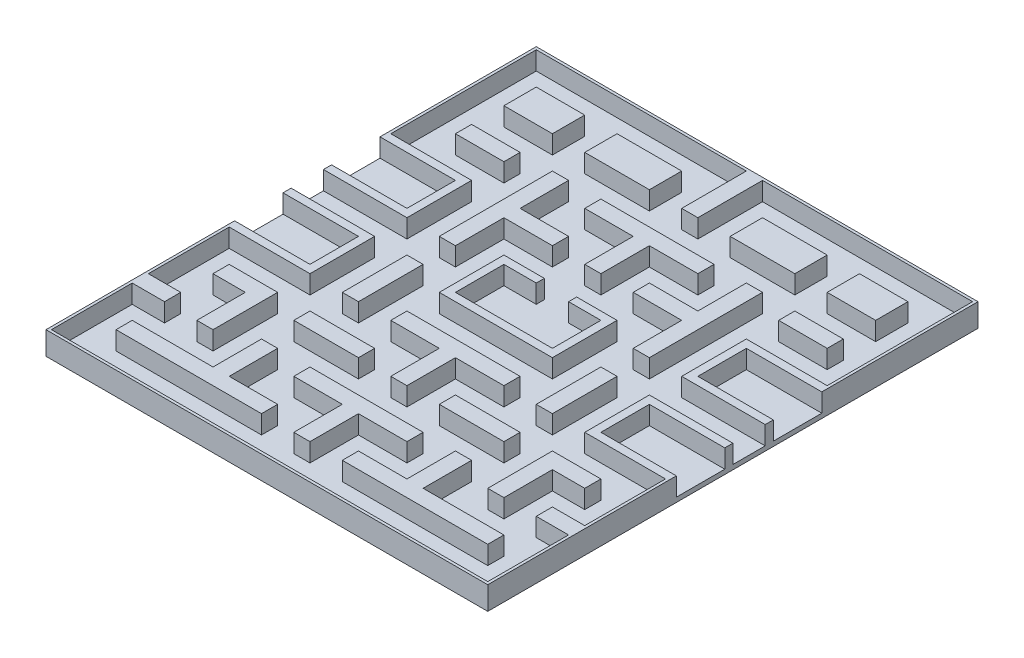
SolidWorks part; units mm, degrees
ref_plane "Front Plane" through (0, 0, 0) normal (0, 0, 1) x (1, 0, 0)
ref_plane "Top Plane" through (0, 0, 0) normal (0, 1, 0) x (1, 0, 0)
ref_plane "Right Plane" through (0, 0, 0) normal (1, 0, 0) x (0, 0, -1)
sketch "Sketch1" plane through (0, 0, 0) normal (0, 1, 0) x (1, 0, 0)
  line L1 (-1244.6, 1600.2) -> (1244.6, 1600.2)
  line L2 (-1244.6, 1600.2) -> (-1244.6, -1600.2)
  line L3 (-1244.6, -1600.2) -> (1244.6, -1600.2)
  line L4 (1244.6, 1600.2) -> (1244.6, -1600.2)
  line L5 (-1244.6, 1600.2) -> (1244.6, -1600.2) construction
  line L6 (-1244.6, -1600.2) -> (1244.6, 1600.2) construction
  point P0 (0, 0)
  dimension "D1" = 3200.4
  dimension "D2" = 2489.2
extrude "Boss-Extrude2" add sketch "Sketch1" along normal blind 25.4
sketch "Sketch5" plane through (0, 25.4, 0) normal (0, 1, 0) x (1, 0, 0)
  line L0 (-1155.7, 1600.2) -> (-1155.7, -1600.2)
  line L1 (1244.6, 1600.2) -> (-1244.6, 1600.2) construction
  line L2 (-1244.6, -1600.2) -> (1244.6, -1600.2) construction
  line L3 (-1244.6, 1600.2) -> (-1244.6, -1600.2) construction
  line L4 (-1066.8, 1600.2) -> (-1066.8, -1600.2)
  line L5 (-977.9, 1600.2) -> (-977.9, -1600.2)
  line L6 (-889, 1600.2) -> (-889, -1600.2)
  line L7 (-800.1, 1600.2) -> (-800.1, -1600.2)
  line L8 (-711.2, 1600.2) -> (-711.2, -1600.2)
  line L9 (-622.3, 1600.2) -> (-622.3, -1600.2)
  line L10 (-533.4, 1600.2) -> (-533.4, -1600.2)
  line L11 (-444.5, 1600.2) -> (-444.5, -1600.2)
  line L12 (-355.6, 1600.2) -> (-355.6, -1600.2)
  line L13 (-266.7, 1600.2) -> (-266.7, -1600.2)
  line L14 (-177.8, 1600.2) -> (-177.8, -1600.2)
  line L15 (-88.9, 1600.2) -> (-88.9, -1600.2)
  line L16 (0, 1600.2) -> (0, -1600.2)
  line L17 (88.9, 1600.2) -> (88.9, -1600.2)
  line L18 (177.8, 1600.2) -> (177.8, -1600.2)
  line L19 (266.7, 1600.2) -> (266.7, -1600.2)
  line L20 (355.6, 1600.2) -> (355.6, -1600.2)
  line L21 (444.5, 1600.2) -> (444.5, -1600.2)
  line L22 (533.4, 1600.2) -> (533.4, -1600.2)
  line L23 (622.3, 1600.2) -> (622.3, -1600.2)
  line L24 (711.2, 1600.2) -> (711.2, -1600.2)
  line L25 (800.1, 1600.2) -> (800.1, -1600.2)
  line L26 (889, 1600.2) -> (889, -1600.2)
  line L27 (977.9, 1600.2) -> (977.9, -1600.2)
  line L28 (1066.8, 1600.2) -> (1066.8, -1600.2)
  line L29 (1155.7, 1600.2) -> (1155.7, -1600.2)
  line L30 (-1244.6, -1511.3) -> (1244.6, -1511.3)
  line L31 (1244.6, -1600.2) -> (1244.6, 1600.2) construction
  line L32 (-1244.6, -1422.4) -> (1244.6, -1422.4)
  line L33 (-1244.6, -1333.5) -> (1244.6, -1333.5)
  line L34 (-1244.6, -1244.6) -> (1244.6, -1244.6)
  line L35 (-1244.6, -1155.7) -> (1244.6, -1155.7)
  line L36 (-1244.6, -1066.8) -> (1244.6, -1066.8)
  line L37 (-1244.6, -977.9) -> (1244.6, -977.9)
  line L38 (-1244.6, -889) -> (1244.6, -889)
  line L39 (-1244.6, -800.1) -> (1244.6, -800.1)
  line L40 (-1244.6, -711.2) -> (1244.6, -711.2)
  line L41 (-1244.6, -622.3) -> (1244.6, -622.3)
  line L42 (-1244.6, -533.4) -> (1244.6, -533.4)
  line L43 (-1244.6, -444.5) -> (1244.6, -444.5)
  line L44 (-1244.6, -355.6) -> (1244.6, -355.6)
  line L45 (-1244.6, -266.7) -> (1244.6, -266.7)
  line L46 (-1244.6, -177.8) -> (1244.6, -177.8)
  line L47 (-1244.6, -88.9) -> (1244.6, -88.9)
  line L48 (-1244.6, 0) -> (1244.6, 0)
  line L49 (-1244.6, 88.9) -> (1244.6, 88.9)
  line L50 (-1244.6, 177.8) -> (1244.6, 177.8)
  line L51 (-1244.6, 266.7) -> (1244.6, 266.7)
  line L52 (-1244.6, 355.6) -> (1244.6, 355.6)
  line L53 (-1244.6, 444.5) -> (1244.6, 444.5)
  line L54 (-1244.6, 533.4) -> (1244.6, 533.4)
  line L55 (-1244.6, 622.3) -> (1244.6, 622.3)
  line L56 (-1244.6, 711.2) -> (1244.6, 711.2)
  line L57 (-1244.6, 800.1) -> (1244.6, 800.1)
  line L58 (-1244.6, 889) -> (1244.6, 889)
  line L59 (-1244.6, 977.9) -> (1244.6, 977.9)
  line L60 (-1244.6, 1066.8) -> (1244.6, 1066.8)
  line L61 (-1244.6, 1155.7) -> (1244.6, 1155.7)
  line L62 (-1244.6, 1244.6) -> (1244.6, 1244.6)
  line L63 (-1244.6, 1333.5) -> (1244.6, 1333.5)
  line L64 (-1244.6, 1422.4) -> (1244.6, 1422.4)
  line L65 (-1244.6, 1511.3) -> (1244.6, 1511.3)
  dimension "D1" = 88.9
  dimension "D3" = 88.9
  dimension "D2" = 27
  dimension "D4" = 35
sketch "Sketch6" plane through (0, 25.4, 0) normal (0, 1, 0) x (1, 0, 0)
  line L0 (-1244.6, 1333.5) -> (1244.6, 1333.5)
  line L1 (-88.9, 222.25) -> (-88.9, 177.8)
  line L2 (755.65, -44.45) -> (755.65, -400.05)
  line L3 (1200.15, -400.05) -> (1200.15, -844.55)
  line L4 (-1244.6, 444.5) -> (1244.6, 444.5) construction
  line L5 (755.65, -400.05) -> (1200.15, -400.05)
  line L6 (-1244.6, 177.8) -> (1244.6, 177.8) construction
  line L7 (755.65, -44.45) -> (1244.6, -44.45)
  line L8 (1244.6, 133.35) -> (755.65, 133.35)
  line L9 (755.65, 488.95) -> (755.65, 133.35)
  line L10 (-1244.6, -88.9) -> (1244.6, -88.9) construction
  line L11 (1200.15, 488.95) -> (755.65, 488.95)
  line L12 (-1244.6, -355.6) -> (1244.6, -355.6) construction
  line L13 (1200.15, 1289.05) -> (1200.15, 488.95)
  line L14 (1244.6, 444.5) -> (1244.6, 1333.5)
  line L15 (1244.6, -1422.4) -> (-1244.6, -1422.4)
  line L16 (-1244.6, -1422.4) -> (-1244.6, -355.6)
  line L17 (-1244.6, -355.6) -> (-800.1, -355.6)
  line L18 (-800.1, 1600.2) -> (-800.1, -1600.2) construction
  line L19 (-800.1, -355.6) -> (-800.1, -88.9)
  line L20 (-800.1, -88.9) -> (-1244.6, -88.9)
  line L21 (-1244.6, -88.9) -> (-1244.6, 177.8)
  line L22 (-1244.6, 177.8) -> (-800.1, 177.8)
  line L23 (-800.1, 177.8) -> (-800.1, 444.5)
  line L24 (-800.1, 444.5) -> (-1244.6, 444.5)
  line L25 (-1244.6, 444.5) -> (-1244.6, 1333.5)
  line L26 (-1200.15, 1289.05) -> (-44.45, 1289.05)
  line L27 (800.1, 444.5) -> (1244.6, 444.5)
  line L28 (-1200.15, 1289.05) -> (-1200.15, 488.95)
  line L29 (-1200.15, 488.95) -> (-755.65, 488.95)
  line L30 (-755.65, 488.95) -> (-755.65, 133.35)
  line L31 (-1244.6, 133.35) -> (-755.65, 133.35)
  line L32 (-755.65, -44.45) -> (-1244.6, -44.45)
  line L33 (-755.65, -400.05) -> (-1200.15, -400.05)
  line L34 (-1200.15, -400.05) -> (-1200.15, -844.55)
  line L35 (-1200.15, -1377.95) -> (1200.15, -1377.95)
  line L36 (-1244.6, 622.3) -> (1244.6, 622.3) construction
  line L37 (800.1, 177.8) -> (800.1, 444.5)
  line L38 (-755.65, -44.45) -> (-755.65, -400.05)
  line L39 (88.9, 177.8) -> (88.9, 222.25)
  line L40 (-1200.15, -844.55) -> (-1022.35, -844.55)
  line L41 (1244.6, 177.8) -> (800.1, 177.8)
  line L42 (1244.6, -88.9) -> (1244.6, 177.8)
  line L43 (800.1, -88.9) -> (1244.6, -88.9)
  line L44 (800.1, -355.6) -> (800.1, -88.9)
  line L45 (1244.6, -355.6) -> (800.1, -355.6)
  line L46 (1244.6, -1422.4) -> (1244.6, -355.6)
  line L47 (177.8, 1600.2) -> (177.8, -1600.2) construction
  line L48 (-1022.35, -844.55) -> (-1022.35, -933.45)
  line L49 (-1022.35, -933.45) -> (-1200.15, -933.45)
  line L50 (-1244.6, -800.1) -> (1244.6, -800.1) construction
  line L51 (-1200.15, -933.45) -> (-1200.15, -1377.95)
  line L52 (1200.15, -844.55) -> (1022.35, -844.55)
  line L53 (1022.35, -933.45) -> (1200.15, -933.45)
  line L54 (1022.35, -844.55) -> (1022.35, -933.45)
  line L55 (1200.15, -933.45) -> (1200.15, -1377.95)
  line L56 (-1022.35, 1111.25) -> (-755.65, 1111.25)
  line L57 (-755.65, 1111.25) -> (-755.65, 933.45)
  line L58 (-755.65, 933.45) -> (-1022.35, 933.45)
  line L59 (-1022.35, 933.45) -> (-1022.35, 1111.25)
  line L60 (-577.85, 1111.25) -> (-222.25, 1111.25)
  line L61 (-222.25, 1111.25) -> (-222.25, 933.45)
  line L62 (-222.25, 933.45) -> (-577.85, 933.45)
  line L63 (-577.85, 933.45) -> (-577.85, 1111.25)
  line L64 (-1022.35, 755.65) -> (-755.65, 755.65)
  line L65 (-755.65, 755.65) -> (-755.65, 666.75)
  line L66 (-755.65, 666.75) -> (-1022.35, 666.75)
  line L67 (-1022.35, 666.75) -> (-1022.35, 755.65)
  line L68 (-577.85, 755.65) -> (-577.85, 133.35)
  line L69 (-577.85, 133.35) -> (-488.95, 133.35)
  line L70 (-488.95, 133.35) -> (-488.95, 400.05)
  line L71 (-488.95, 400.05) -> (-222.25, 400.05)
  line L72 (-222.25, 400.05) -> (-222.25, 488.95)
  line L73 (-222.25, 488.95) -> (-488.95, 488.95)
  line L74 (-488.95, 488.95) -> (-488.95, 755.65)
  line L75 (-488.95, 755.65) -> (-577.85, 755.65)
  line L76 (-1244.6, 800.1) -> (1244.6, 800.1) construction
  line L77 (-577.85, -44.45) -> (-488.95, -44.45)
  line L78 (-488.95, -44.45) -> (-488.95, -400.05)
  line L79 (-488.95, -400.05) -> (-577.85, -400.05)
  line L80 (-577.85, -400.05) -> (-577.85, -44.45)
  line L81 (-622.3, 1600.2) -> (-622.3, -1600.2) construction
  line L82 (-844.55, -933.45) -> (-755.65, -933.45)
  line L83 (-577.85, -577.85) -> (-222.25, -577.85)
  line L84 (-222.25, -577.85) -> (-222.25, -666.75)
  line L85 (-222.25, -666.75) -> (-577.85, -666.75)
  line L86 (-577.85, -666.75) -> (-577.85, -577.85)
  line L87 (-1244.6, -533.4) -> (1244.6, -533.4) construction
  line L88 (-755.65, -577.85) -> (-1022.35, -577.85)
  line L89 (-1022.35, -577.85) -> (-1022.35, -666.75)
  line L90 (-1022.35, -666.75) -> (-844.55, -666.75)
  line L91 (-844.55, -666.75) -> (-844.55, -933.45)
  line L92 (-755.65, -933.45) -> (-755.65, -577.85)
  line L93 (-1066.8, 1600.2) -> (-1066.8, -1600.2) construction
  line L94 (-577.85, -844.55) -> (-577.85, -1111.25)
  line L95 (-577.85, -1111.25) -> (-1022.35, -1111.25)
  line L96 (-1022.35, -1111.25) -> (-1022.35, -1200.15)
  line L97 (-1022.35, -1200.15) -> (-222.25, -1200.15)
  line L98 (-222.25, -1200.15) -> (-222.25, -1111.25)
  line L99 (-222.25, -1111.25) -> (-488.95, -1111.25)
  line L100 (-488.95, -1111.25) -> (-488.95, -844.55)
  line L101 (-488.95, -844.55) -> (-577.85, -844.55)
  line L102 (-1244.6, -1066.8) -> (1244.6, -1066.8) construction
  line L103 (-311.15, -400.05) -> (-311.15, -311.15)
  line L104 (-311.15, -311.15) -> (311.15, -311.15)
  line L105 (-311.15, -400.05) -> (-44.45, -400.05)
  line L106 (-44.45, -400.05) -> (-44.45, -666.75)
  line L107 (-44.45, -666.75) -> (44.45, -666.75)
  line L108 (-1244.6, -444.5) -> (1244.6, -444.5) construction
  line L109 (-355.6, 1600.2) -> (-355.6, -1600.2) construction
  line L110 (-311.15, -844.55) -> (311.15, -844.55)
  line L111 (-311.15, -844.55) -> (-311.15, -933.45)
  line L112 (-311.15, -933.45) -> (-44.45, -933.45)
  line L113 (-44.45, -933.45) -> (-44.45, -1200.15)
  line L114 (-44.45, -1200.15) -> (44.45, -1200.15)
  line L115 (-311.15, 755.65) -> (311.15, 755.65)
  line L116 (-311.15, 755.65) -> (-311.15, 666.75)
  line L117 (-311.15, 666.75) -> (-44.45, 666.75)
  line L118 (-44.45, 400.05) -> (44.45, 400.05)
  line L119 (-44.45, 400.05) -> (-44.45, 666.75)
  line L120 (355.6, 1600.2) -> (355.6, -1600.2) construction
  line L121 (-311.15, -133.35) -> (-311.15, 222.25)
  line L122 (-311.15, 222.25) -> (-88.9, 222.25)
  line L123 (-88.9, 1600.2) -> (-88.9, -1600.2) construction
  line L124 (-311.15, -133.35) -> (311.15, -133.35)
  line L125 (-1244.6, 266.7) -> (1244.6, 266.7) construction
  line L126 (-88.9, 177.8) -> (-266.7, 177.8)
  line L127 (-266.7, 1600.2) -> (-266.7, -1600.2) construction
  line L128 (-266.7, 177.8) -> (-266.7, -88.9)
  line L129 (-266.7, -88.9) -> (266.7, -88.9)
  line L130 (-44.45, 933.45) -> (-44.45, 1289.05)
  line L131 (-44.45, 933.45) -> (44.45, 933.45)
  line L132 (-1244.6, 889) -> (1244.6, 889) construction
  line L133 (44.45, -933.45) -> (44.45, -1200.15)
  line L134 (311.15, -933.45) -> (44.45, -933.45)
  line L135 (311.15, -844.55) -> (311.15, -933.45)
  line L136 (488.95, -844.55) -> (577.85, -844.55)
  line L137 (488.95, -1111.25) -> (488.95, -844.55)
  line L138 (577.85, -844.55) -> (577.85, -1111.25)
  line L139 (222.25, -1111.25) -> (488.95, -1111.25)
  line L140 (222.25, -1200.15) -> (222.25, -1111.25)
  line L141 (1022.35, -1200.15) -> (222.25, -1200.15)
  line L142 (1022.35, -1111.25) -> (1022.35, -1200.15)
  line L143 (577.85, -1111.25) -> (1022.35, -1111.25)
  line L144 (844.55, -933.45) -> (755.65, -933.45)
  line L145 (844.55, -666.75) -> (844.55, -933.45)
  line L146 (755.65, -933.45) -> (755.65, -577.85)
  line L147 (1022.35, -666.75) -> (844.55, -666.75)
  line L148 (1022.35, -577.85) -> (1022.35, -666.75)
  line L149 (755.65, -577.85) -> (1022.35, -577.85)
  line L150 (577.85, -666.75) -> (577.85, -577.85)
  line L151 (222.25, -666.75) -> (577.85, -666.75)
  line L152 (577.85, -577.85) -> (222.25, -577.85)
  line L153 (44.45, -400.05) -> (44.45, -666.75)
  line L154 (311.15, -400.05) -> (44.45, -400.05)
  line L155 (311.15, -400.05) -> (311.15, -311.15)
  line L156 (222.25, -577.85) -> (222.25, -666.75)
  line L157 (577.85, -400.05) -> (577.85, -44.45)
  line L158 (488.95, -400.05) -> (577.85, -400.05)
  line L159 (488.95, -44.45) -> (488.95, -400.05)
  line L160 (577.85, -44.45) -> (488.95, -44.45)
  line L161 (266.7, 177.8) -> (266.7, -88.9)
  line L162 (88.9, 177.8) -> (266.7, 177.8)
  line L163 (311.15, 222.25) -> (88.9, 222.25)
  line L164 (311.15, -133.35) -> (311.15, 222.25)
  line L165 (44.45, 400.05) -> (44.45, 666.75)
  line L166 (311.15, 666.75) -> (44.45, 666.75)
  line L167 (311.15, 755.65) -> (311.15, 666.75)
  line L168 (488.95, 755.65) -> (577.85, 755.65)
  line L169 (488.95, 488.95) -> (488.95, 755.65)
  line L170 (222.25, 488.95) -> (488.95, 488.95)
  line L171 (222.25, 400.05) -> (222.25, 488.95)
  line L172 (488.95, 400.05) -> (222.25, 400.05)
  line L173 (488.95, 133.35) -> (488.95, 400.05)
  line L174 (577.85, 133.35) -> (488.95, 133.35)
  line L175 (577.85, 755.65) -> (577.85, 133.35)
  line L176 (1022.35, 666.75) -> (1022.35, 755.65)
  line L177 (755.65, 666.75) -> (1022.35, 666.75)
  line L178 (755.65, 755.65) -> (755.65, 666.75)
  line L179 (1022.35, 755.65) -> (755.65, 755.65)
  line L180 (44.45, 933.45) -> (44.45, 1289.05)
  line L181 (577.85, 933.45) -> (577.85, 1111.25)
  line L182 (222.25, 933.45) -> (577.85, 933.45)
  line L183 (222.25, 1111.25) -> (222.25, 933.45)
  line L184 (577.85, 1111.25) -> (222.25, 1111.25)
  line L185 (1022.35, 933.45) -> (1022.35, 1111.25)
  line L186 (755.65, 933.45) -> (1022.35, 933.45)
  line L187 (755.65, 1111.25) -> (755.65, 933.45)
  line L188 (1022.35, 1111.25) -> (755.65, 1111.25)
  line L189 (44.45, 1289.05) -> (1200.15, 1289.05)
  line L190 (-1244.6, 1155.7) -> (1244.6, 1155.7) construction
  line L191 (711.2, 1600.2) -> (711.2, -1600.2) construction
  line L192 (1155.7, 1600.2) -> (1155.7, -1600.2) construction
  line L193 (88.9, 1600.2) -> (88.9, -1600.2) construction
  line L194 (1244.6, -1600.2) -> (1244.6, 1600.2) construction
  line L195 (-1244.6, -977.9) -> (1244.6, -977.9) construction
  line L196 (444.5, 1600.2) -> (444.5, -1600.2) construction
  line L197 (622.3, 1600.2) -> (622.3, -1600.2) construction
  line L198 (266.7, 1600.2) -> (266.7, -1600.2) construction
  line L199 (0, 1600.2) -> (0, -1600.2) construction
  line L200 (-1244.6, -1244.6) -> (1244.6, -1244.6) construction
  line L201 (-1244.6, 0) -> (1244.6, 0) construction
  line L202 (1066.8, 1600.2) -> (1066.8, -1600.2) construction
  line L203 (-1244.6, 88.9) -> (1244.6, 88.9) construction
  line L204 (977.9, 1600.2) -> (977.9, -1600.2) construction
  line L205 (-1244.6, -711.2) -> (1244.6, -711.2) construction
  point P77 (1200.15, -844.55)
  point P78 (1200.15, -933.45)
  point P88 (-1022.35, 711.2)
  point P93 (-533.4, 755.65)
  point P174 (0, -1200.15)
  point P176 (0, -844.55)
  point P196 (0, -666.75)
  point P199 (0, -311.15)
  point P204 (0, -133.35)
  point P205 (0, -88.9)
  point P210 (0, 400.05)
  point P213 (0, 755.65)
  point P227 (0, 933.45)
  point P236 (-44.45, 1289.05)
  point P237 (44.45, 1289.05)
  line M20 (1244.6, -1600.2) -> (1244.6, 1600.2)
  line M22 (-1244.6, 1600.2) -> (-1244.6, -1600.2)
  dimension "D1" = 44.45
  dimension "D2" = 44.45
  dimension "D3" = 44.45
  dimension "D4" = 88.9
  dimension "D5" = 44.45
  dimension "D6" = 44.45
  dimension "D7" = 44.45
  dimension "D8" = 44.45
  dimension "D9" = 44.45
  dimension "D10" = 177.8
  dimension "D11" = 355.6
  dimension "D12" = 177.8
  dimension "D13" = 177.8
  dimension "D14" = 177.8
  dimension "D15" = 266.7
  dimension "D16" = 177.8
  dimension "D17" = 355.6
  dimension "D18" = 177.8
  dimension "D19" = 177.8
  dimension "D20" = 266.7
  dimension "D21" = 88.9
  dimension "D22" = 88.9
  dimension "D23" = 44.45
  dimension "D24" = 88.9
  dimension "D25" = 266.7
  dimension "D26" = 266.7
  dimension "D27" = 88.9
  dimension "D28" = 44.45
  dimension "D29" = 355.6
  dimension "D30" = 88.9
  dimension "D31" = 44.45
  dimension "D32" = 44.45
  dimension "D33" = 88.9
  dimension "D34" = 355.6
  dimension "D35" = 44.45
  dimension "D36" = 177.8
  dimension "D37" = 355.6
  dimension "D38" = 88.9
  dimension "D39" = 88.9
  dimension "D40" = 44.45
  dimension "D41" = 44.45
  dimension "D42" = 44.45
  dimension "D43" = 88.9
  dimension "D44" = 800.1
  dimension "D45" = 88.9
  dimension "D46" = 266.7
  dimension "D47" = 44.45
  dimension "D48" = 44.45
  dimension "D49" = 266.7
  dimension "D50" = 44.45
  dimension "D51" = 88.9
  dimension "D52" = 44.45
  dimension "D53" = 266.7
  dimension "D54" = 266.7
  dimension "D55" = 88.9
  dimension "D56" = 44.45
  dimension "D57" = 266.7
  dimension "D58" = 266.7
  dimension "D59" = 88.9
  dimension "D60" = 44.45
  dimension "D61" = 355.6
  dimension "D62" = 44.45
  dimension "D63" = 44.45
  dimension "D64" = 355.6
  dimension "D65" = 88.9
  dimension "D66" = 355.6
  dimension "D67" = 177.8
  dimension "D68" = 44.45
  dimension "D69" = 44.45
  dimension "D70" = 355.6
  dimension "D71" = 177.8
  dimension "D72" = 44.45
  dimension "D73" = 44.45
  dimension "D74" = 266.7
  dimension "D75" = 177.8
  dimension "D76" = 177.8
  dimension "D77" = 266.7
  dimension "D78" = 800.1
  dimension "D79" = 889
  dimension "D80" = 44.45
  dimension "D81" = 444.5
  dimension "D82" = 444.5
  dimension "D83" = 88.9
  dimension "D84" = 44.45
  dimension "D85" = 44.45
  dimension "D86" = 266.7
  dimension "D87" = 88.9
  dimension "D88" = 88.9
  dimension "D89" = 266.7
  dimension "D90" = 266.7
  dimension "D91" = 44.45
  dimension "D92" = 44.45
  dimension "D93" = 266.7
  dimension "D94" = 266.7
  dimension "D95" = 266.7
  dimension "D96" = 44.45
  dimension "D97" = 44.45
  dimension "D98" = 622.3
  dimension "D99" = 88.9
  dimension "D100" = 44.45
  dimension "D101" = 266.7
  dimension "D102" = 88.9
  dimension "D103" = 44.45
  dimension "D104" = 44.45
  dimension "D105" = 88.9
  dimension "D106" = 177.8
  dimension "D107" = 44.45
  dimension "D108" = 355.6
  dimension "D109" = 266.7
  dimension "D110" = 44.45
  dimension "D111" = 44.45
  dimension "D112" = 44.45
  dimension "D113" = 355.6
  dimension "D114" = 88.9
  dimension "D115" = 355.6
  dimension "D116" = 88.9
  dimension "D117" = 44.45
  dimension "D118" = 266.7
  dimension "D119" = 444.5
  dimension "D120" = 44.45
  dimension "D121" = 444.5
  dimension "D122" = 90
  dimension "D123" = 266.7
  dimension "D124" = 488.95
  dimension "D125" = 355.6
  dimension "D126" = 444.5
  dimension "D127" = 266.7
  dimension "D128" = 444.5
  dimension "D129" = 444.5
  dimension "D130" = 44.45
  dimension "D131" = 44.45
  dimension "D132" = 44.45
  dimension "D133" = 266.7
  dimension "D134" = 266.7
  dimension "D135" = 90
  dimension "D136" = 88.9
  dimension "D137" = 44.45
  dimension "D138" = 90
  dimension "D139" = 90
  dimension "D140" = 90
  dimension "D141" = 90
  dimension "D142" = 44.45
  dimension "D143" = 44.45
  dimension "D144" = 44.45
  dimension "D145" = 44.45
  dimension "D146" = 44.45
  dimension "D147" = 44.45
  dimension "D148" = 44.45
  dimension "D149" = 44.45
  dimension "D150" = 266.7
  dimension "D151" = 88.9
  dimension "D152" = 177.8
  dimension "D153" = 88.9
  dimension "D154" = 90
  dimension "D155" = 90
  dimension "D156" = 90
  dimension "D157" = 90
  dimension "D158" = 44.45
  dimension "D159" = 44.45
  dimension "D164" = 44.45
  dimension "D165" = 44.45
  dimension "D166" = 44.45
  dimension "D167" = 44.45
  dimension "D168" = 44.45
  dimension "D169" = 44.45
  dimension "D170" = 44.45
  dimension "D171" = 44.45
  dimension "D172" = 44.45
  dimension "D173" = 44.45
  dimension "D174" = 44.45
extrude "Boss-Extrude3" add sketch "Sketch6" along normal blind 101.6 contours L180 L189 L13 L11 L9 L8 L41 L37 L27 L0 L24 L23 L22 L31 L30 L29 L28 L26 L130 L131 M20 M22 | L59 L58 L57 L56 | L63 L62 L61 L60 | L181 L184 L183 L182 | L185 L188 L187 L186 | L176 L179 L178 L177 | L175 L168 L169 L170 L171 L172 L173 L174 | L167 L115 L116 L117 L119 L118 L165 L166 | L74 L75 L68 L69 L70 L71 L72 L73 | L67 L66 L65 L64 | L124 L164 L163 L39 L162 L161 L129 L128 L126 L1 L122 L121 | L80 L79 L78 L77 | L53 L55 L35 L51 L49 L48 L40 L34 L33 L38 L32 L20 L19 L17 L15 L45 L44 L43 L7 L2 L5 L3 L52 L54 M22 M20 | L154 L155 L104 L103 L105 L106 L107 L153 | L157 L160 L159 L158 | L152 L156 L151 L150 | L149 L146 L144 L145 L147 L148 | L143 L138 L136 L137 L139 L140 L141 L142 | L135 L110 L111 L112 L113 L114 L133 L134 | L100 L101 L94 L95 L96 L97 L98 L99 | L82 L92 L88 L89 L90 L91 | L86 L85 L84 L83
sketch "Sketch8" plane through (0, 127, 0) normal (0, 1, 0) x (1, 0, 0)
  line L0 (-1244.6, 1333.5) -> (-1244.6, 444.5) construction
  line L1 (-1244.6, 1303.8633) -> (1244.6, 1303.8633)
  line L2 (-1244.6, 1303.8633) -> (-1244.6, 1600.2)
  line L3 (-1244.6, 1600.2) -> (1244.6, 1600.2)
  line L4 (1244.6, 1303.8633) -> (1244.6, 1600.2)
  dimension "D1" = 296.3367
extrude "Cut-Extrude1" cut sketch "Sketch8" against normal through all
sketch "Sketch9" plane through (0, 127, 0) normal (0, 1, 0) x (1, 0, 0)
  line L0 (-1244.6, -355.6) -> (-1244.6, -1422.4) construction
  line L1 (-1244.6, -1392.7633) -> (1244.6, -1392.7633)
  line L2 (-1244.6, -1392.7633) -> (-1244.6, -1600.2)
  line L3 (-1244.6, -1600.2) -> (1244.6, -1600.2)
  line L4 (1244.6, -1392.7633) -> (1244.6, -1600.2)
  line L5 (-1200.15, -1377.95) -> (1200.15, -1377.95) construction
  dimension "D1" = 14.8133
extrude "Cut-Extrude2" cut sketch "Sketch9" against normal through all and the other way through all
sketch "Sketch10" plane through (0, 127, 0) normal (0, 1, 0) x (1, 0, 0)
  line L0 (1244.6, -1392.7633) -> (-1244.6, -1392.7633) construction
  line L1 (-1244.6, 1303.8633) -> (-1214.9633, 1303.8633)
  line L2 (-1244.6, 1303.8633) -> (-1244.6, -1392.7633)
  line L3 (-1244.6, -1392.7633) -> (-1214.9633, -1392.7633)
  line L4 (-1214.9633, 1303.8633) -> (-1214.9633, -1392.7633)
  line L5 (-1200.15, -933.45) -> (-1200.15, -1377.95) construction
  dimension "D1" = 14.8133
extrude "Cut-Extrude3" cut sketch "Sketch10" against normal through all
sketch "Sketch11" plane through (0, 127, 0) normal (0, 1, 0) x (1, 0, 0)
  line L0 (-1214.9633, 1303.8633) -> (1244.6, 1303.8633) construction
  line L1 (1214.9633, 1303.8633) -> (1244.6, 1303.8633)
  line L2 (1214.9633, 1303.8633) -> (1214.9633, -1392.7633)
  line L3 (1214.9633, -1392.7633) -> (1244.6, -1392.7633)
  line L4 (1244.6, 1303.8633) -> (1244.6, -1392.7633)
  line L5 (1200.15, -933.45) -> (1200.15, -1377.95) construction
  dimension "D1" = 14.8133
extrude "Cut-Extrude4" cut sketch "Sketch11" against normal through all
